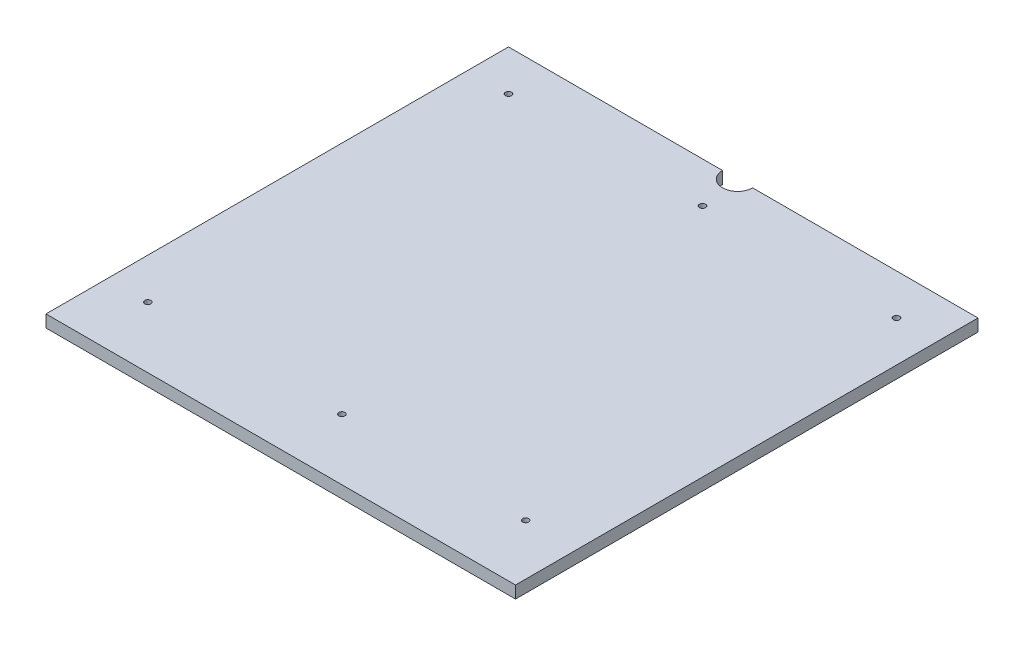
SolidWorks part; units mm, degrees
ref_plane "前视基准面" through (0, 0, 0) normal (0, 0, 1) x (1, 0, 0)
ref_plane "上视基准面" through (0, 0, 0) normal (0, 1, 0) x (1, 0, 0)
ref_plane "右视基准面" through (0, 0, 0) normal (1, 0, 0) x (0, 0, -1)
sketch "草图1" plane through (0, 0, 0) normal (0, 1, 0) x (1, 0, 0)
  line L0 (-112.725, 93.5) -> (117.725, 93.5) construction
  line L1 (-112.725, 113.5) -> (-7.6626, 113.5)
  line L2 (-112.725, 113.5) -> (-112.725, -113.5)
  line L3 (-112.725, -113.5) -> (117.725, -113.5)
  line L4 (117.725, 113.5) -> (117.725, -113.5)
  line L5 (-112.725, -83.5) -> (117.725, -83.5) construction
  line L6 (7.5, 113.5) -> (117.725, 113.5)
  line L7 (7.1026, 113.5) -> (7.5, 113.5)
  circle A0 centre (-92.725, 93.5) radius 1.5
  circle A1 centre (97.725, 93.5) radius 1.5
  circle A2 centre (2.5, 93.5) radius 1.5
  circle A3 centre (-92.725, -83.5) radius 1.5
  circle A4 centre (2.5, -83.5) radius 1.5
  circle A5 centre (92.725, -83.5) radius 1.5
  arc A7 (-7.6626, 113.5) -> (7.1026, 113.5) centre (-0.28, 113.5) ccw
  dimension "D7" = 3
  dimension "D9" = 3
  dimension "D11" = 3
  dimension "D12" = 3
  dimension "D13" = 3
  dimension "D14" = 3
  dimension "D15" = 2.78
  dimension "D1" = 230.45
  dimension "D2" = 227
  dimension "D3" = 112.725
  dimension "D4" = 113.5
  dimension "D5" = 20
  dimension "D6" = 30
  dimension "D8" = 20
  dimension "D10" = 20
extrude "凸台-拉伸1" add sketch "草图1" along normal blind 6
